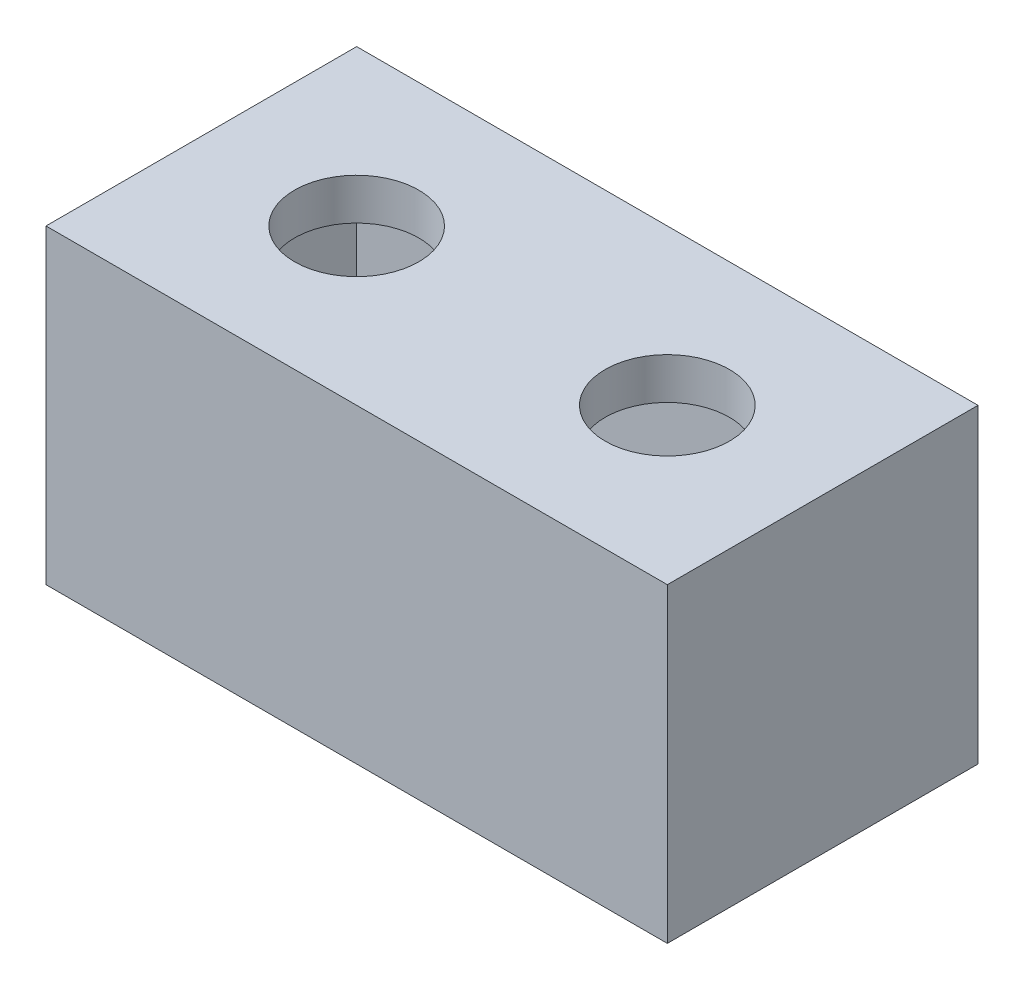
SolidWorks part; units mm, degrees
ref_plane "Front Plane" through (0, 0, 0) normal (0, 0, 1) x (1, 0, 0)
ref_plane "Top Plane" through (0, 0, 0) normal (0, 1, 0) x (1, 0, 0)
ref_plane "Right Plane" through (0, 0, 0) normal (1, 0, 0) x (0, 0, -1)
sketch "Sketch1" plane through (0, 0, 0) normal (0, 1, 0) x (1, 0, 0)
  line L1 (0, 0) -> (30, 0)
  line L2 (0, 0) -> (0, 15)
  line L3 (0, 15) -> (30, 15)
  line L4 (30, 0) -> (30, 15)
  dimension "D1" = 30
  dimension "D2" = 15
extrude "Boss-Extrude1" add sketch "Sketch1" along normal blind 15 contours L3 L4 L1 L2
sketch "Sketch2" plane through (0, 0, 0) normal (0, -1, 0) x (1, 0, 0)
  line L0 (0, 0) -> (30, 0) construction
  line L1 (2, -2) -> (28, -2)
  line L2 (2, -2) -> (2, -13)
  line L3 (2, -13) -> (28, -13)
  line L4 (28, -2) -> (28, -13)
  line L5 (0, 0) -> (0, -15) construction
  line L6 (0, -15) -> (30, -15) construction
  line L7 (30, 0) -> (30, -15) construction
  dimension "D1" = 2
  dimension "D2" = 2
  dimension "D3" = 2
  dimension "D4" = 2
extrude "Cut-Extrude1" cut sketch "Sketch2" against normal blind 13
sketch "Sketch3" plane through (0, 15, 0) normal (0, 1, 0) x (1, 0, 0)
  line L0 (0, 0) -> (30, 0) construction
  line L1 (30, 0) -> (30, 15) construction
  line L2 (0, 0) -> (0, 15) construction
  circle A0 centre (7.5, 7.5) radius 3
  circle A1 centre (22.5, 7.5) radius 3
  dimension "D1" = 6
  dimension "D2" = 6
  dimension "D4" = 7.5
  dimension "D5" = 7.5
  dimension "D3" = 7.5
  dimension "D6" = 7.5
extrude "Cut-Extrude2" cut sketch "Sketch3" against normal blind 13
sketch "Sketch4" plane through (0, 0, -15) normal (0, 0, -1) x (-1, 0, 0)
  line L0 (0, 0) -> (-30, 0) construction
  circle A0 centre (-15, 0) radius 5
  dimension "D1" = 10
extrude "Cut-Extrude3" cut sketch "Sketch4" against normal blind 5
